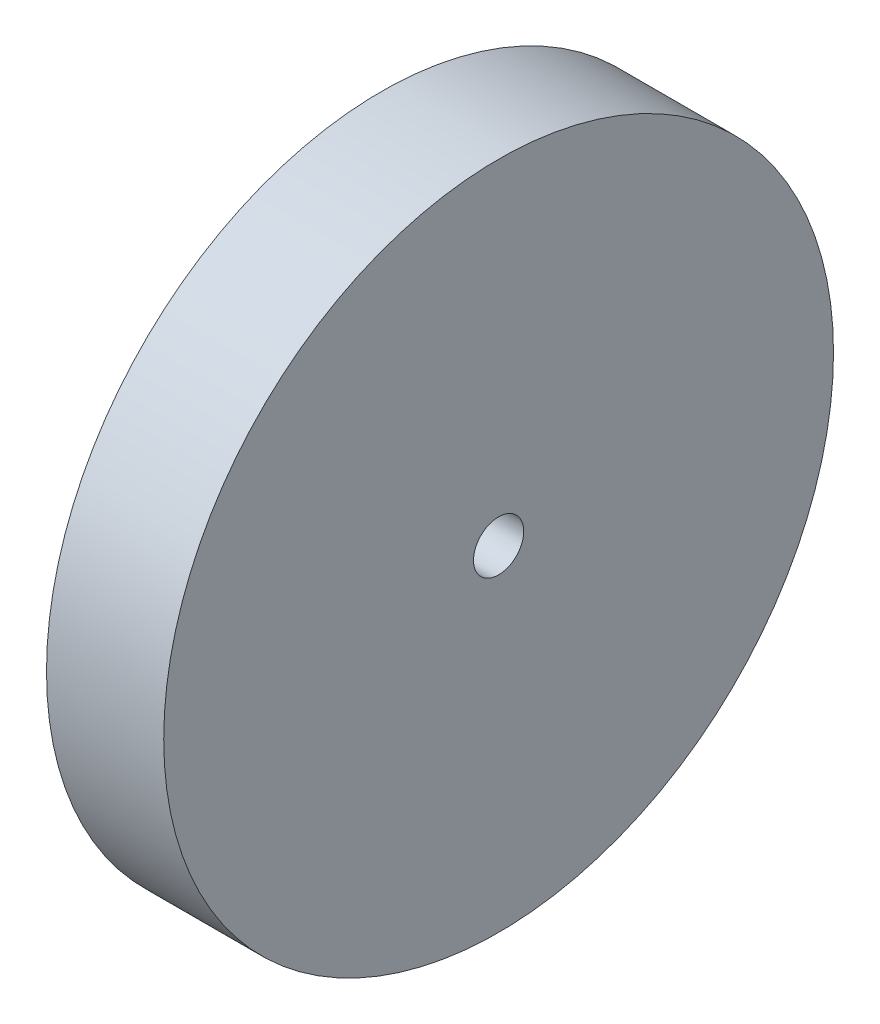
SolidWorks part; units mm, degrees
ref_plane "Front Plane" through (0, 0, 0) normal (1, 0, 0) x (0, 1, 0)
ref_plane "Top Plane" through (0, 0, 0) normal (0, 0, 1) x (0, 1, 0)
ref_plane "Right Plane" through (0, 0, 0) normal (0, 1, 0) x (-1, 0, 0)
sketch "Sketch1" plane through (0, 0, 0) normal (1, 0, 0) x (0, 1, 0)
  circle A0 centre (0, 0) radius 20
  dimension "D1" = 40
extrude "Boss-Extrude1" add sketch "Sketch1" along normal mid plane 7
sketch "Sketch2" plane through (3.5, 0, 0) normal (1, 0, 0) x (0, 1, 0)
  circle A0 centre (0, 0) radius 1.5
  dimension "D1" = 3
extrude "Cut-Extrude1" cut sketch "Sketch2" against normal blind 7
